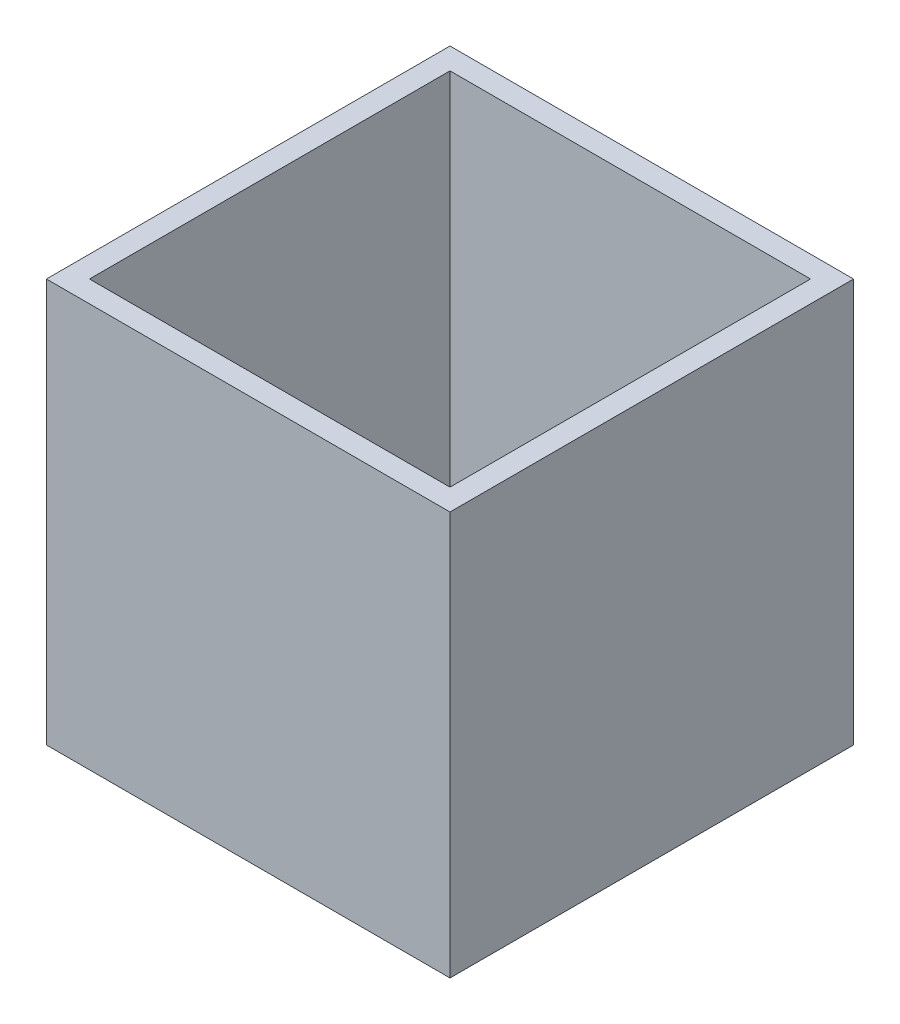
SolidWorks part; units mm, degrees
ref_plane "Front Plane" through (0, 0, 0) normal (0, 0, 1) x (1, 0, 0)
ref_plane "Top Plane" through (0, 0, 0) normal (0, 1, 0) x (1, 0, 0)
ref_plane "Right Plane" through (0, 0, 0) normal (1, 0, 0) x (0, 0, -1)
sketch "Sketch1" plane through (0, 0, 0) normal (0, 1, 0) x (1, 0, 0)
  line L1 (0, 0) -> (150, 0)
  line L2 (0, 0) -> (0, 150)
  line L3 (0, 150) -> (150, 150)
  line L4 (150, 0) -> (150, 150)
  dimension "D1" = 150
  dimension "D2" = 150
extrude "Boss-Extrude1" add sketch "Sketch1" along normal blind 150
sketch "Sketch9" plane through (0, 150, 0) normal (0, 1, 0) x (1, 0, 0)
  line L1 (142, 142) -> (8, 142)
  line L2 (142, 142) -> (142, 8)
  line L3 (142, 8) -> (8, 8)
  line L4 (8, 142) -> (8, 8)
  line L5 (75, 8) -> (75, 142) construction
  line L6 (142, 75) -> (8, 75) construction
  point P0 (75, 75)
  dimension "D1" = 134
  dimension "D2" = 134
extrude "Cut-Extrude1" cut sketch "Sketch9" against normal offset from surface (142 mm away) 142 up to face at (75, 150, -75)
